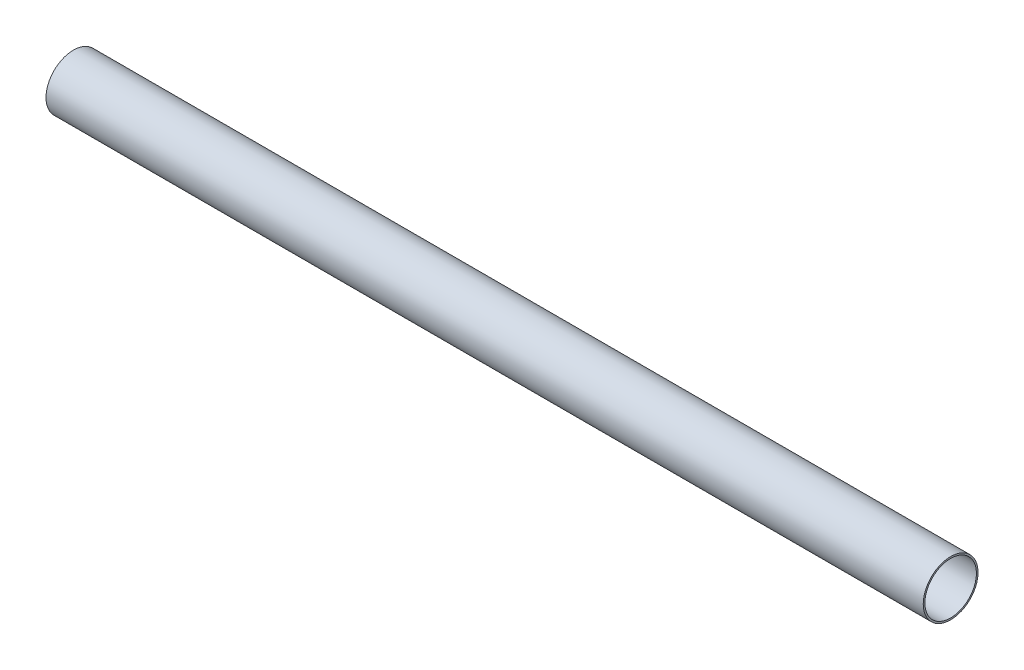
SolidWorks part; units mm, degrees
ref_plane "Plan de face" through (0, 0, 0) normal (0, 0, 1) x (1, 0, 0)
ref_plane "Plan de dessus" through (0, 0, 0) normal (0, 1, 0) x (1, 0, 0)
ref_plane "Plan de droite" through (0, 0, 0) normal (1, 0, 0) x (0, 0, -1)
sketch "Esquisse1" plane through (0, 0, 0) normal (0, 0, 1) x (1, 0, 0)
  line L0 (-151.4152, 0) -> (161.143, 0) construction
  line L2 (-55, 2.5) -> (25, 2.5)
  line L3 (-55, 2.5) -> (-55, 2.35)
  line L4 (-55, 2.35) -> (25, 2.35)
  line L5 (25, 2.5) -> (25, 2.35)
  dimension "D1" = 2.5
  dimension "D2" = 80
  dimension "D3" = 0.15
  dimension "D4" = 25
revolve "Révolution1" add sketch "Esquisse1" angle 360 about L0
